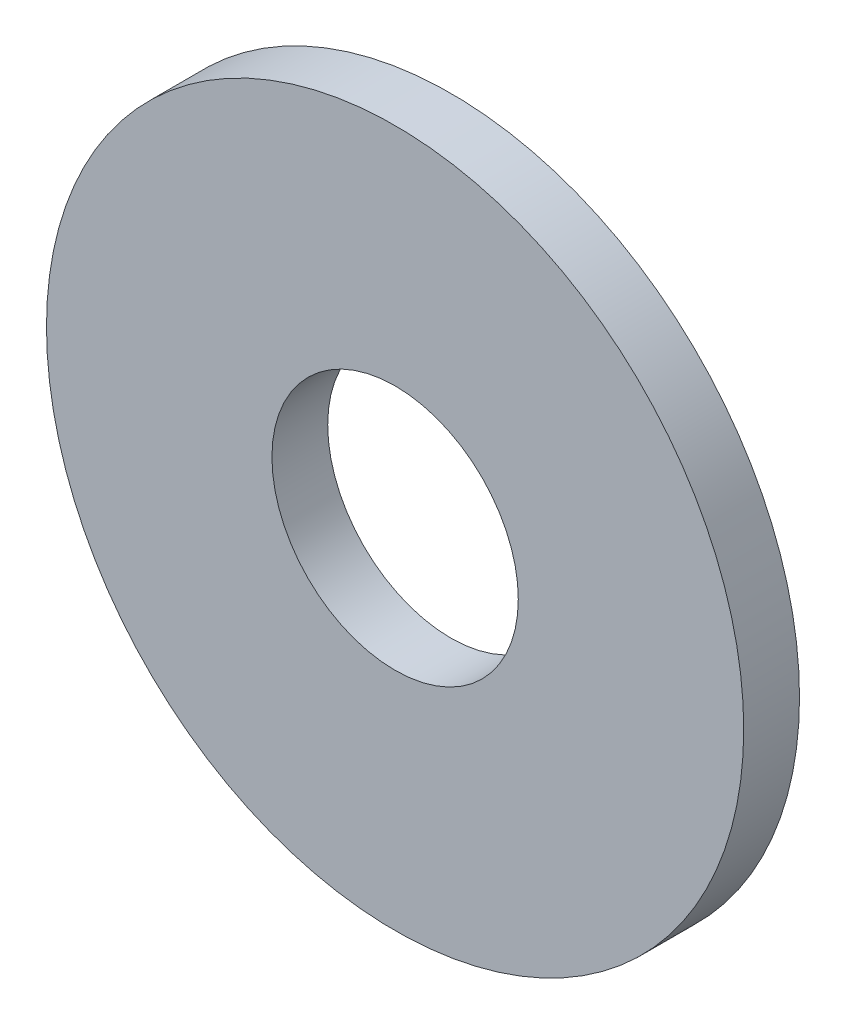
SolidWorks part; units mm, degrees
ref_plane "前视基准面" through (0, 0, 0) normal (0, 0, 1) x (1, 0, 0)
ref_plane "上视基准面" through (0, 0, 0) normal (0, 1, 0) x (1, 0, 0)
ref_plane "右视基准面" through (0, 0, 0) normal (1, 0, 0) x (0, 0, -1)
other "Configuration Table"
sketch "草图1" plane through (0, 0, 0) normal (1, 0, 0) x (0, 0, -1)
  line L0 (-5, 0) -> (6.2, 0) construction
  line L1 (1.2, 2.65) -> (1.2, 7.5)
  line L2 (1.2, 7.5) -> (0, 7.5)
  line L3 (0, 7.5) -> (0, 2.65)
  line L4 (0, 2.65) -> (1.2, 2.65)
revolve "旋转1" add sketch "草图1" angle 360 about L0
